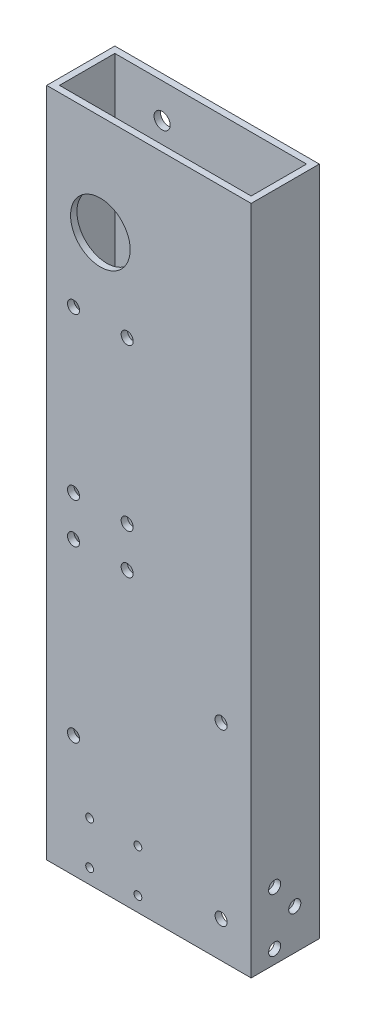
SolidWorks part; units mm, degrees
material "6061-T6 (SS)"
ref_plane "Front Plane" through (0, 0, 0) normal (0, 0, 1) x (1, 0, 0)
ref_plane "Top Plane" through (0, 0, 0) normal (0, 1, 0) x (1, 0, 0)
ref_plane "Right Plane" through (0, 0, 0) normal (1, 0, 0) x (0, 0, -1)
sketch "Sketch1" plane through (0, 0, 0) normal (0, 1, 0) x (1, 0, 0)
  line L1 (-76.2, 25.4) -> (76.2, 25.4)
  line L2 (-76.2, 25.4) -> (-76.2, -25.4)
  line L3 (-76.2, -25.4) -> (76.2, -25.4)
  line L4 (76.2, 25.4) -> (76.2, -25.4)
  line L5 (-76.2, 25.4) -> (76.2, -25.4) construction
  line L6 (-76.2, -25.4) -> (76.2, 25.4) construction
  point P0 (0, 0)
  dimension "D1" = 152.4
  dimension "D2" = 50.8
extrude "Extrude-Thin1" add sketch "Sketch1" along normal blind 500 thin
hole_wizard "M8 Clearance Hole1" positions "Sketch3" profile "Sketch4" hole size "M8" standard "ANSI Metric" end condition through all
sketch "Sketch3" plane through (0, 0, 25.4) normal (0, 0, 1) x (1, 0, 0)
  line L0 (-76.2, 227) -> (3.8, 227)
  line L1 (-76.2, 500) -> (-76.2, 0) construction
  line L3 (-76.2, 0) -> (76.2, 0) construction
  line L4 (3.8, 227) -> (3.8, 387)
  line L5 (3.8, 387) -> (-76.2, 387)
  line L6 (-76.2, 387) -> (-76.2, 227)
  line L8 (-56.2, 217) -> (-16.2, 217)
  line L11 (-56.2, 217) -> (-56.2, 153.6667)
  line L12 (-56.2, 153.6667) -> (-56.2, 90.3333)
  line L13 (-56.2, 90.3333) -> (-56.2, 27)
  line L15 (-36.2, 217) -> (-36.2, 227)
  line L17 (-56.2, 27) -> (53.8, 27)
  line L18 (53.8, 27) -> (53.8, 153.6667)
  line L19 (53.8, 153.6667) -> (-56.2, 153.6667)
  line L22 (-56.2, 90.3333) -> (-76.2, 90.3333)
  line L27 (-36.2, 425) -> (-36.2, 387)
  circle A0 centre (-36.2, 425) radius 49.2125
  point P18 (-56.2, 217)
  point P19 (-16.2, 217)
  point P26 (-56.2, 90.3333)
  point P35 (53.8, 27)
  point P36 (53.8, 153.6667)
  dimension "D9" = 98.425
  dimension "D1" = 200
  dimension "D2" = 80
  dimension "D3" = 160
  dimension "D4" = 27
  dimension "D5" = 10
  dimension "D6" = 40
  dimension "D7" = 110
  dimension "D8" = 38
sketch "Sketch4" plane through (53.8, 153.6667, 25.4) normal (1, 0, 0) x (0, -1, 0)
  line L0 (0, 0) -> (0, 50.8)
  line L1 (0, 50.8) -> (4.5, 50.8)
  line L2 (4.5, 50.8) -> (4.5, 0)
  line L5 (4.5, 0) -> (0, 0)
  line L11 (0, -6.35) -> (0, 107.95) construction
  dimension "Thru Hole Dia." = 9
  dimension "Thru Hole Depth" = 50.8
hole_wizard "M8 Clearance Hole2" positions "Sketch5" profile "Sketch6" hole size "M8" standard "ANSI Metric" end condition through all
sketch "Sketch5" plane through (0, 0, 25.4) normal (0, 0, 1) x (1, 0, 0)
  line L1 (-56.2, 367) -> (-16.2, 367)
  line L2 (-56.2, 367) -> (-56.2, 247)
  line L3 (-56.2, 247) -> (-16.2, 247)
  line L4 (-16.2, 367) -> (-16.2, 247)
  line L5 (-56.2, 217) -> (-16.2, 217) construction
  line L6 (-36.2, 227) -> (-36.2, 247)
  line L7 (-76.2, 227) -> (3.8, 227) construction
  point P1 (-56.2, 367)
  point P2 (-16.2, 247)
  point P153 (-56.2, 247)
  point P154 (-16.2, 367)
  dimension "D1" = 20
  dimension "D2" = 120
sketch "Sketch6" plane through (-56.2, 367, 25.4) normal (1, 0, 0) x (0, -1, 0)
  line L0 (0, 0) -> (0, 50.8)
  line L1 (0, 50.8) -> (4.5, 50.8)
  line L2 (4.5, 50.8) -> (4.5, 0)
  line L5 (4.5, 0) -> (0, 0)
  line L11 (0, -6.35) -> (0, 107.95) construction
  dimension "Thru Hole Dia." = 9
  dimension "Thru Hole Depth" = 50.8
hole_wizard "Ø12.0 (12) Diameter Hole1" positions "Sketch7" profile "Sketch8" hole size "Ø12.0" standard "ANSI Metric"
sketch "Sketch7" plane through (0, 0, -25.4) normal (0, 0, -1) x (-1, 0, 0)
  line L0 (-13.0125, 425) -> (36.2, 375.7875)
  line L3 (-13.0125, 425) -> (36.2, 474.2125)
  line L4 (36.2, 474.2125) -> (85.4125, 425)
  line L5 (85.4125, 425) -> (36.2, 375.7875)
  line L7 (36.2, 425) -> (36.2, 387) construction
  circle A0 centre (36.2, 425) radius 49.2125 construction
  point P0 (36.2, 375.7875)
  point P4 (-13.0125, 425)
  point P6 (36.2, 474.2125)
sketch "Sketch8" plane through (-36.2, 375.7875, -25.4) normal (1, 0, 0) x (0, 1, 0)
  line L0 (0, 0) -> (0, 4.7625)
  line L1 (0, 4.7625) -> (6, 4.7625)
  line L2 (6, 4.7625) -> (6, 0)
  line L5 (6, 0) -> (0, 0)
  line L11 (0, -6.35) -> (0, 107.95) construction
  dimension "Thru Hole Dia." = 12
  dimension "Thru Hole Depth" = 4.7625
sketch "Sketch9" plane through (0, 0, 0) normal (0, 0, 1) x (1, 0, 0)
  circle A0 centre (-36.2, 425) radius 22.225
  dimension "D1" = 44.45
extrude "Cut-Extrude1" cut sketch "Sketch9" against normal through all and the other way through all
hole_wizard "M5 Clearance Hole1" positions "Sketch10" profile "Sketch11" hole size "M5" standard "ANSI Metric" end condition through all
sketch "Sketch10" plane through (0, 0, 25.4) normal (0, 0, 1) x (1, 0, 0)
  line L1 (-8.2, 43) -> (-44.2, 43)
  line L2 (-8.2, 43) -> (-8.2, 11)
  line L3 (-8.2, 11) -> (-44.2, 11)
  line L4 (-44.2, 43) -> (-44.2, 11)
  line L5 (-8.2, 43) -> (-44.2, 11) construction
  line L6 (-8.2, 11) -> (-44.2, 43) construction
  line L8 (-56.2, 27) -> (53.8, 27) construction
  line L9 (-76.2, 500) -> (-76.2, 0) construction
  point P2 (-44.2, 11)
  point P107 (-8.2, 43)
  point P108 (-8.2, 11)
  point P109 (-44.2, 43)
  point P114 (-26.2, 27)
  dimension "D1" = 36
  dimension "D2" = 32
  dimension "D3" = 50
sketch "Sketch11" plane through (-44.2, 11, 25.4) normal (1, 0, 0) x (0, -1, 0)
  line L0 (0, 0) -> (0, 50.8)
  line L1 (0, 50.8) -> (2.9, 50.8)
  line L2 (2.9, 50.8) -> (2.9, 0)
  line L5 (2.9, 0) -> (0, 0)
  line L11 (0, -6.35) -> (0, 107.95) construction
  dimension "Thru Hole Dia." = 5.8
  dimension "Thru Hole Depth" = 50.8
hole_wizard "M8 Clearance Hole3" positions "Sketch12" profile "Sketch14" hole size "M8" standard "ANSI Metric"
sketch "Sketch12" plane through (76.2, 0, 0) normal (1, 0, 0) x (0, 0, -1)
  line L1 (-7.9, 50) -> (7.1, 50)
  line L2 (-7.9, 50) -> (-7.9, 10)
  line L3 (-7.9, 10) -> (7.1, 10)
  line L4 (7.1, 50) -> (7.1, 10)
  line L5 (-25.4, 0) -> (25.4, 0) construction
  line L6 (-25.4, 90.3333) -> (-25.4, 27) construction
  point P1 (-7.9, 50)
  point P87 (-7.9, 10)
  point P98 (7.1, 30)
  dimension "D1" = 10
  dimension "D2" = 17.5
  dimension "D3" = 15
  dimension "D4" = 40
sketch "Sketch14" plane through (76.2, 50, 7.9) normal (0, 1, 0) x (0, 0, -1)
  line L0 (0, 0) -> (0, 4.7625)
  line L1 (0, 4.7625) -> (4.5, 4.7625)
  line L2 (4.5, 4.7625) -> (4.5, 0)
  line L5 (4.5, 0) -> (0, 0)
  line L11 (0, -6.35) -> (0, 107.95) construction
  dimension "Thru Hole Dia." = 9
  dimension "Thru Hole Depth" = 4.7625
hole_wizard "Ø20.0 (20) Diameter Hole1" positions "Sketch15" profile "Sketch16" hole size "Ø20.0" standard "ANSI Metric"
sketch "Sketch15" plane through (-76.2, 0, 0) normal (-1, 0, 0) x (0, 0, 1)
  line L0 (7.9, 50) -> (-7.1, 30)
  point P0 (0.4, 40)
  point P7 (7.9, 50)
  point P9 (-7.1, 30)
sketch "Sketch16" plane through (-76.2, 40, 0.4) normal (0, 1, 0) x (0, 0, 1)
  line L0 (0, 0) -> (0, 4.7625)
  line L1 (0, 4.7625) -> (10, 4.7625)
  line L2 (10, 4.7625) -> (10, 0)
  line L5 (10, 0) -> (0, 0)
  line L11 (0, -6.35) -> (0, 107.95) construction
  dimension "Thru Hole Dia." = 20
  dimension "Thru Hole Depth" = 4.7625
